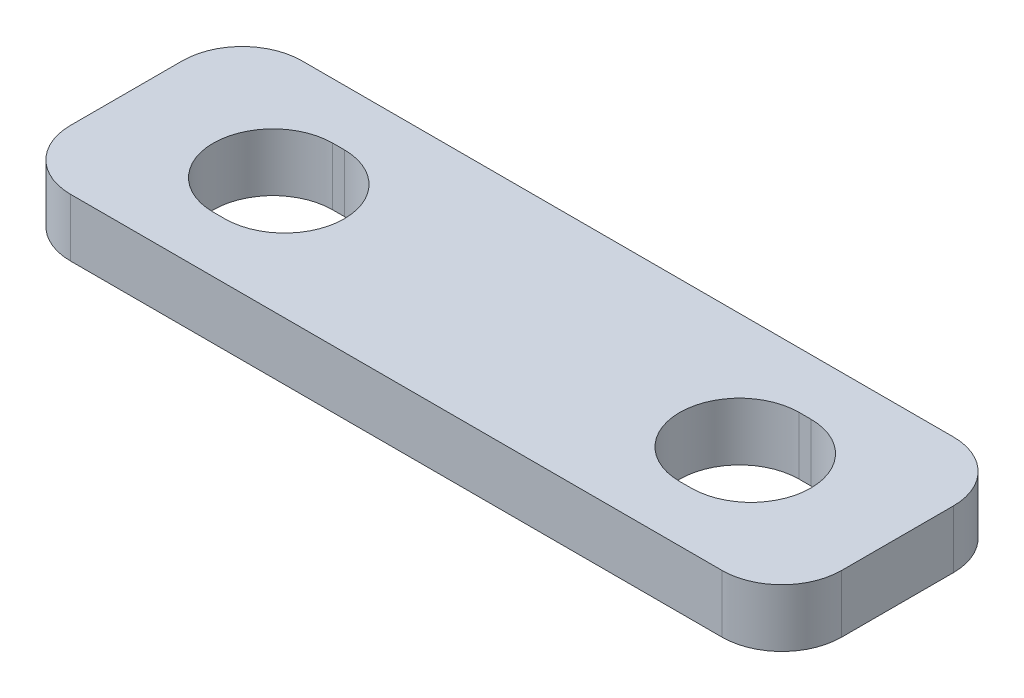
SolidWorks part; units mm, degrees
ref_plane "前视基准面" through (0, 0, 0) normal (0, 0, 1) x (1, 0, 0)
ref_plane "上视基准面" through (0, 0, 0) normal (0, 1, 0) x (1, 0, 0)
ref_plane "右视基准面" through (0, 0, 0) normal (1, 0, 0) x (0, 0, -1)
sketch "草图1" plane through (0, 0, 0) normal (0, 1, 0) x (1, 0, 0)
  line L0 (0, 0) -> (20, 0)
  line L2 (20, 6) -> (0, 6)
  line L3 (0, 6) -> (0, 0)
  line L4 (16.2, 3) -> (15.9, 3) construction
  line L5 (16.2, 1.45) -> (15.9, 1.45)
  line L6 (16.2, 4.55) -> (15.9, 4.55)
  line L7 (10, 8.8074) -> (10, -4.7604) construction
  line L8 (3.8, 3) -> (4.1, 3) construction
  line L9 (3.8, 1.45) -> (4.1, 1.45)
  line L10 (3.8, 4.55) -> (4.1, 4.55)
  line L11 (20, 6) -> (20, 0)
  arc A2 (16.2, 1.45) -> (16.2, 4.55) centre (16.2, 3) ccw
  arc A3 (15.9, 4.55) -> (15.9, 1.45) centre (15.9, 3) ccw
  arc A4 (3.8, 1.45) -> (3.8, 4.55) centre (3.8, 3) cw
  arc A5 (4.1, 4.55) -> (4.1, 1.45) centre (4.1, 3) cw
  point P7 (16.05, 3)
  point P16 (3.95, 3)
  point P22 (10, 0)
  point P23 (10, 6)
  dimension "D3" = 5.9
  dimension "D5" = 1.55
  dimension "D1" = 10
  dimension "D2" = 6
  dimension "D4" = 0.3
extrude "凸台-拉伸1" add sketch "草图1" along normal blind 1.5
fillet "圆角1" radius 1.55 4 edges at (0, 0.75, 0) (0, 0.75, -6) (20, 0.75, 0) (20, 0.75, -6)
